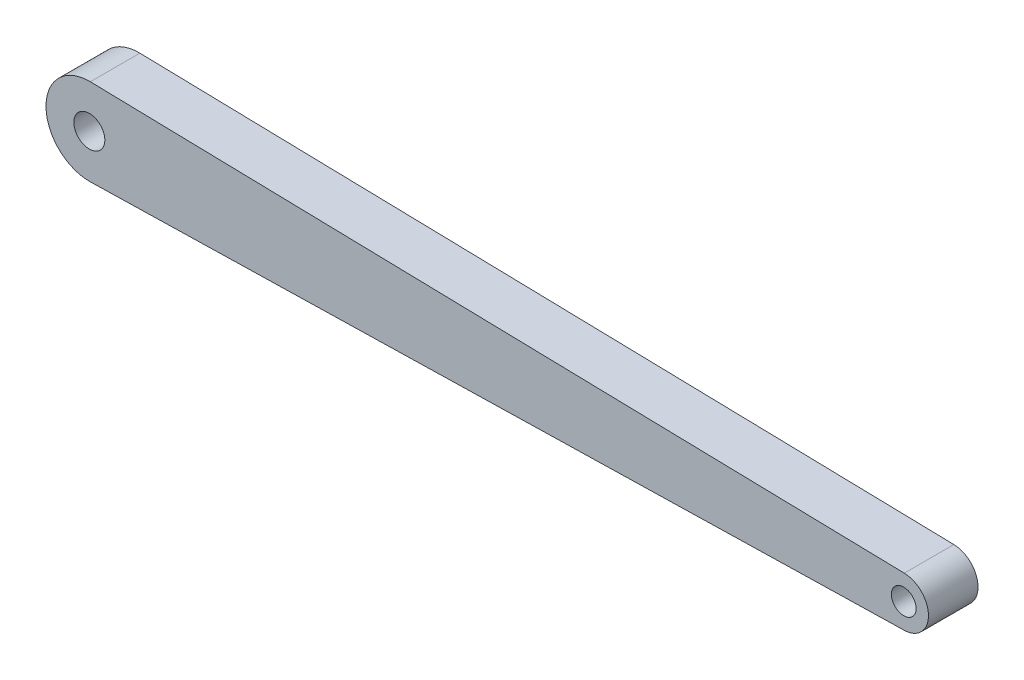
SolidWorks part; units mm, degrees
ref_plane "Front Plane" through (0, 0, 0) normal (0, 0, 1) x (1, 0, 0)
ref_plane "Top Plane" through (0, 0, 0) normal (0, 1, 0) x (1, 0, 0)
ref_plane "Right Plane" through (0, 0, 0) normal (1, 0, 0) x (0, 0, -1)
sketch "Sketch1" plane through (0, 0, 0) normal (0, 0, 1) x (1, 0, 0)
  line L0 (-1315, 0) -> (0, 0) construction
  line L1 (-1313.403, 69.9818) -> (0.9125, 39.9896)
  line L2 (0.9125, -39.9896) -> (-1313.403, -69.9818)
  circle A0 centre (0, 0) radius 20
  circle A1 centre (-1315, 0) radius 25
  arc A2 (-1313.403, -69.9818) -> (-1313.403, 69.9818) centre (-1315, 0) cw
  arc A3 (0.9125, -39.9896) -> (0.9125, 39.9896) centre (0, 0) ccw
  point P10 (0, 0)
  dimension "D2" = 50
  dimension "D3" = 40
  dimension "D4" = 70
  dimension "D5" = 40
  dimension "D1" = 1315
extrude "Boss-Extrude1" add sketch "Sketch1" along normal mid plane 80
